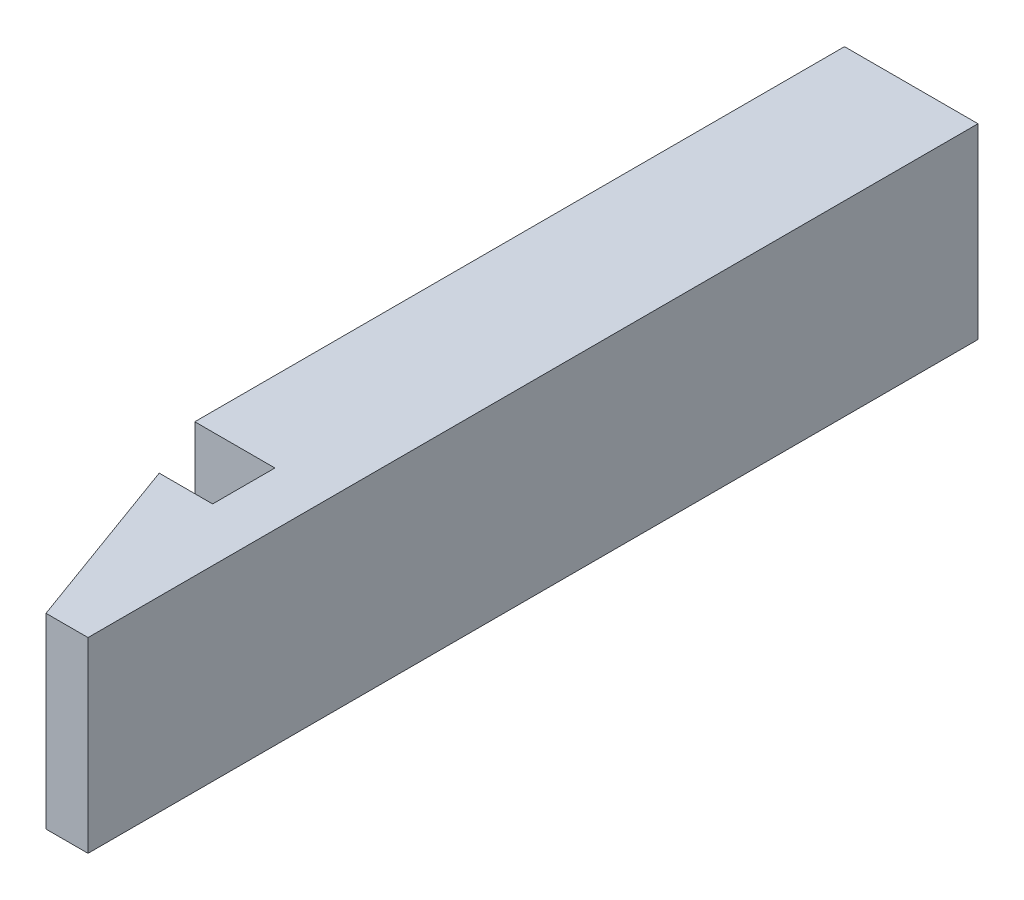
SolidWorks part; units mm, degrees
ref_plane "Front Plane" through (0, 0, 0) normal (0, 0, 1) x (1, 0, 0)
ref_plane "Top Plane" through (0, 0, 0) normal (0, 1, 0) x (1, 0, 0)
ref_plane "Right Plane" through (0, 0, 0) normal (1, 0, 0) x (0, 0, -1)
sketch "Sketch2" plane through (0, 0, 0) normal (0, 1, 0) x (1, 0, 0)
  line L1 (0, 0) -> (3.81, 0)
  line L2 (0, 0) -> (0, 25.4)
  line L3 (0, 25.4) -> (3.81, 25.4)
  line L4 (3.81, 0) -> (3.81, 25.4)
  dimension "D1" = 3.81
  dimension "D2" = 25.4
extrude "Boss-Extrude1" add sketch "Sketch2" along normal blind 5.334
sketch "Sketch3" plane through (0, 5.334, 0) normal (0, 1, 0) x (1, 0, 0)
  line L1 (0, 25.4) -> (0, 0) construction
  line L2 (0.762, 5.08) -> (2.611, 0)
  line L3 (0, 0) -> (3.81, 0) construction
  line L4 (2.611, 0) -> (3.81, 0)
  line L5 (3.81, 0) -> (3.81, 25.4)
  line L6 (3.81, 25.4) -> (0, 25.4)
  line L7 (0, 25.4) -> (0, 6.858)
  line L8 (0, 6.858) -> (2.286, 6.858)
  line L9 (2.286, 6.858) -> (2.286, 5.08)
  line L10 (2.286, 5.08) -> (0.762, 5.08)
  dimension "D1" = 2.286
  dimension "D2" = 5.08
  dimension "D3" = 1.778
  dimension "D4" = 0.762
  dimension "D5" = 20
extrude "Cut-Extrude1" cut sketch "Sketch3" against normal through all flip side to cut
